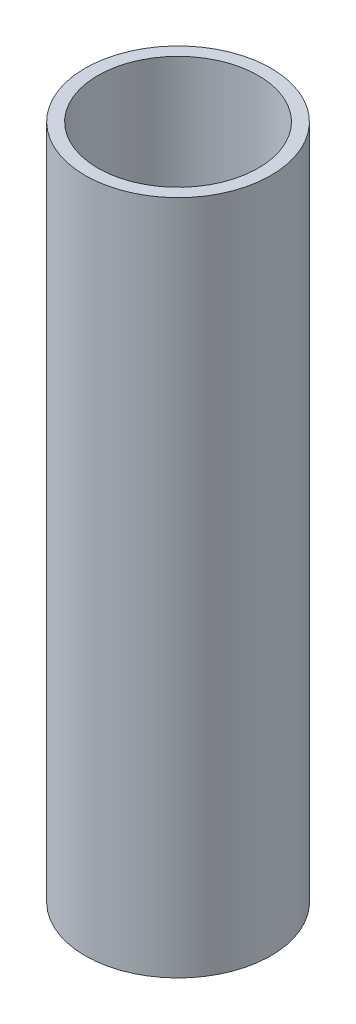
SolidWorks part; units mm, degrees
material "PVC 0.007 Plasticized"
ref_plane "Front Plane" through (0, 0, 0) normal (0, 0, 1) x (1, 0, 0)
ref_plane "Top Plane" through (0, 0, 0) normal (0, 1, 0) x (1, 0, 0)
ref_plane "Right Plane" through (0, 0, 0) normal (1, 0, 0) x (0, 0, -1)
sketch "Sketch1" plane through (0, 0, 0) normal (0, 1, 0) x (1, 0, 0)
  circle A0 centre (0, 0) radius 11
  circle A1 centre (0, 0) radius 9.5
extrude "Boss-Extrude1" add sketch "Sketch1" along normal blind 80
